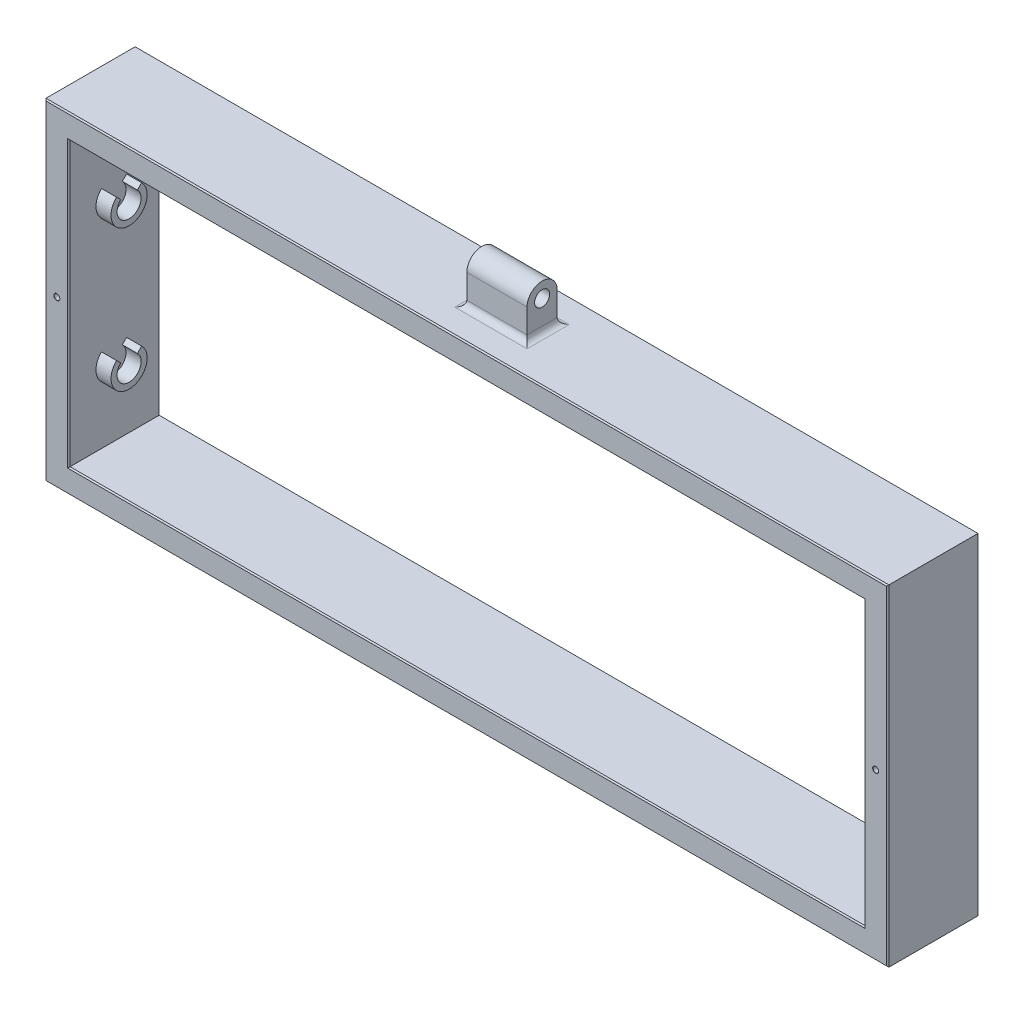
SolidWorks part; units mm, degrees
material "TPU (Thermoplastic polyurethane)"
ref_plane "Front Plane" through (0, 0, 0) normal (0, 0, 1) x (1, 0, 0)
ref_plane "Top Plane" through (0, 0, 0) normal (0, 1, 0) x (1, 0, 0)
ref_plane "Right Plane" through (0, 0, 0) normal (1, 0, 0) x (0, 0, -1)
sketch "Sketch1" plane through (0, 0, 0) normal (0, 0, 1) x (1, 0, 0)
  line L1 (-70, 27.5) -> (70, 27.5)
  line L2 (-70, 27.5) -> (-70, -27.5)
  line L3 (-70, -27.5) -> (70, -27.5)
  line L4 (70, 27.5) -> (70, -27.5)
  line L5 (-70, 27.5) -> (70, -27.5) construction
  line L6 (-70, -27.5) -> (70, 27.5) construction
  line L7 (-66, 23.5) -> (66, 23.5)
  line L8 (-66, 23.5) -> (-66, -23.5)
  line L9 (-66, -23.5) -> (66, -23.5)
  line L10 (66, 23.5) -> (66, -23.5)
  line L11 (-66, 23.5) -> (66, -23.5) construction
  line L12 (-66, -23.5) -> (66, 23.5) construction
  point P0 (0, 0)
  point P7 (0, 0)
  dimension "D1" = 140
  dimension "D2" = 55
  dimension "D3" = 132
  dimension "D4" = 47
extrude "Rectangle Pad" add sketch "Sketch1" along normal blind 15
sketch "Sketch2" plane through (66, 0, 0) normal (-1, 0, 0) x (0, 0, 1)
  line L2 (7.5, 23.5) -> (7.5, -23.5) construction
  line L3 (8.875, 13.2024) -> (9.5823, 13.9097)
  line L4 (6.125, 13.2024) -> (5.4177, 13.9097)
  line L5 (15, -23.5) -> (0, -23.5) construction
  line L6 (15, 23.5) -> (0, 23.5) construction
  line L7 (8.875, -10.2976) -> (9.5823, -9.5903)
  line L8 (6.125, -10.2976) -> (5.4177, -9.5903)
  arc A3 (5.4177, 13.9097) -> (9.5823, 13.9097) centre (7.5, 11.75) ccw
  arc A4 (6.125, 13.2024) -> (8.875, 13.2024) centre (7.5, 11.75) ccw
  arc A5 (5.4177, -9.5903) -> (9.5823, -9.5903) centre (7.5, -11.75) ccw
  arc A6 (6.125, -10.2976) -> (8.875, -10.2976) centre (7.5, -11.75) ccw
  dimension "D3" = 2.75
  dimension "D4" = 45
  dimension "D1" = 3
  dimension "D2" = 2
  dimension "D7" = 3
  dimension "D8" = 2
  dimension "D5" = 45
  dimension "D6" = 11.75
  dimension "D9" = 2.75
  dimension "D10" = 11.75
  dimension "D11" = 45
extrude "MountingHoles" add sketch "Sketch2" along normal blind 2.5
mirror "Mirror1" about plane through (0, 0, 0) normal (1, 0, 0) of "MountingHoles"
sketch "Sketch3" plane through (0, 0, 15) normal (0, 0, 1) x (1, 0, 0)
  line L0 (-70, 29.9126) -> (-66, 29.9126) construction
  line L1 (-70, 27.5) -> (-70, -27.5) construction
  line L2 (-66, 23.5) -> (-66, -23.5) construction
  line L3 (-68, 29.9126) -> (-68, -33.4831) construction
  line L4 (0, 0) -> (94.0259, 0) construction
  line L5 (94.0259, 0) -> (-99.0249, 0) construction
  line L6 (66, 23.5) -> (70, 23.5) construction
  line L7 (70, -27.5) -> (70, 27.5) construction
  line L8 (68, 23.5) -> (68, -33.4831) construction
  point P22 (-68, 0)
  point P24 (68, 0)
hole_wizard "Tap Drill for M1.2x0.25 Tap2" positions "Sketch3" profile "Sketch5" hole size "M1.2x0.25" standard "ANSI Metric" end condition through all
sketch "Sketch5" plane through (68, 0, 15) normal (1, 0, 0) x (0, -1, 0)
  line L0 (0, 0) -> (0, 15)
  line L1 (0, 15) -> (0.475, 15)
  line L2 (0.475, 15) -> (0.475, 0.025)
  line L3 (0.475, 0.025) -> (0.5, 0)
  line L5 (0.5, 0) -> (0, 0)
  line L6 (-0.475, 0.025) -> (-0.5, 0) construction
  line L11 (0, -6.35) -> (0, 107.95) construction
  dimension "Thru Hole Dia." = 0.95
  dimension "Thru Hole Depth" = 15
  dimension "Near C'Sink Dia." = 1
  dimension "Near C'Sink Angle" = 90
chamfer "Chamfer3" distance 0.2 angle 45 8 edges at (0, 23.5, 15) (66, 0, 15) (0, -23.5, 15) (-66, 0, 15) (-70, 0, 15) (0, -27.5, 15) (70, 0, 15) (0, 27.5, 15)
ref_plane "Plane1" through (-5, 0, 0) normal (1, 0, 0) x (0, 0, -1)
sketch "Sketch6" plane through (-5, 0, 0) normal (1, 0, 0) x (0, 0, -1)
  line L0 (-7.4, 27.5) -> (-7.4, 39.0349) construction
  line L1 (-9.9, 32.5) -> (-9.9, 27.5)
  line L2 (-14.8, 27.5) -> (0, 27.5) construction
  line L3 (-9.9, 27.5) -> (-4.9, 27.5)
  line L4 (-4.9, 27.5) -> (-4.9, 32.5)
  arc A0 (-9.9, 32.5) -> (-4.9, 32.5) centre (-7.4, 32.5) cw
  dimension "D2" = 2.5
  dimension "D1" = 5
  dimension "D3" = 5
extrude "Boss-Extrude1" add sketch "Sketch6" along normal blind 10
fillet "Fillet1" radius 1 4 edges at (0, 27.5, 9.9) (-5, 27.5, 7.4) (0, 27.5, 4.9) (5, 27.5, 7.4)
sketch "Sketch7" plane through (-5, 0, 0) normal (-1, 0, 0) x (0, 0, 1)
  line L0 (4.9, 32.5) -> (9.9, 32.5) construction
  line L1 (4.9, 28.5) -> (4.9, 32.5) construction
  line L2 (9.9, 32.5) -> (9.9, 28.5) construction
  line L3 (7.4, 35) -> (7.4, 28.5) construction
  line L4 (4.9, 28.5) -> (9.9, 28.5) construction
  arc A0 (9.9, 32.5) -> (4.9, 32.5) centre (7.4, 32.5) ccw construction
  circle A1 centre (7.4, 32.5) radius 1.25
  dimension "D2" = 2.5
  dimension "D1" = 4
extrude "Cut-Extrude1" cut sketch "Sketch7" against normal blind 10
